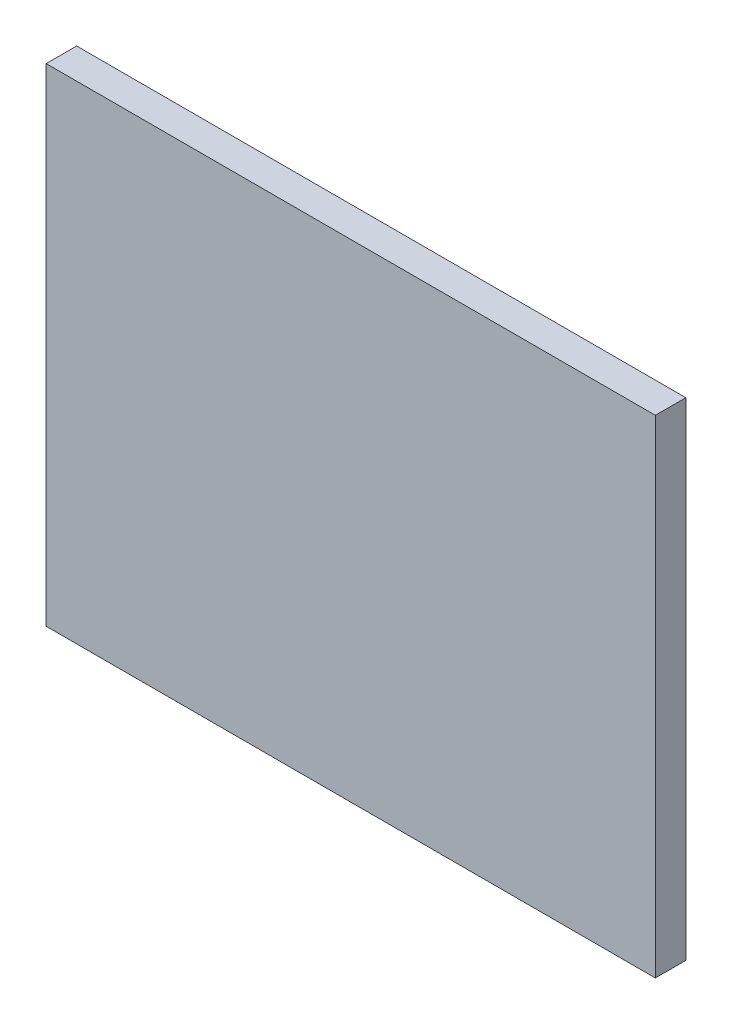
SolidWorks part; units mm, degrees
ref_plane "Front Plane" through (0, 0, 0) normal (0, 0, 1) x (1, 0, 0)
ref_plane "Top Plane" through (0, 0, 0) normal (0, 1, 0) x (1, 0, 0)
ref_plane "Right Plane" through (0, 0, 0) normal (1, 0, 0) x (0, 0, -1)
sketch "Sketch1" plane through (0, 0, 0) normal (0, 0, 1) x (1, 0, 0)
  line L1 (-52.7642, 32.7642) -> (47.2358, 32.7642)
  line L2 (-52.7642, 32.7642) -> (-52.7642, -47.2358)
  line L3 (-52.7642, -47.2358) -> (47.2358, -47.2358)
  line L4 (47.2358, 32.7642) -> (47.2358, -47.2358)
  dimension "D1" = 100
  dimension "D2" = 80
extrude "Boss-Extrude1" add sketch "Sketch1" along normal blind 5
ref_plane "Plane1" through (-52.7642, 32.7642, 5) normal (0, -1, 0) x (-1, 0, 0)
